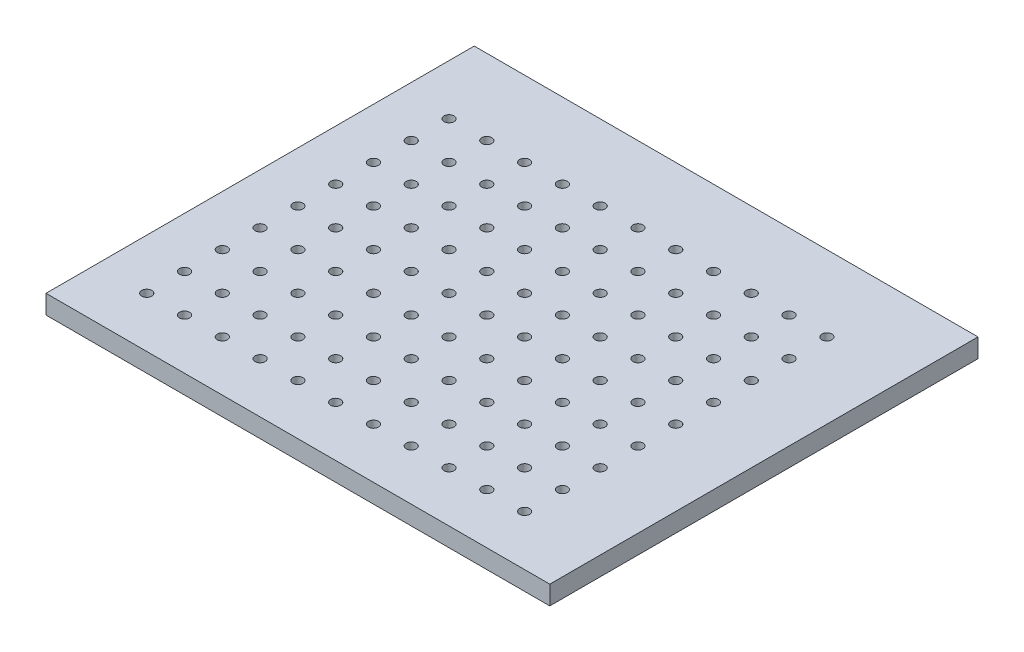
SolidWorks part; units mm, degrees
ref_plane "Plano frontal" through (0, 0, 0) normal (0, 0, 1) x (1, 0, 0)
ref_plane "Plano superior" through (0, 0, 0) normal (0, 1, 0) x (1, 0, 0)
ref_plane "Plano direito" through (0, 0, 0) normal (1, 0, 0) x (0, 0, -1)
sketch "Esboço1" plane through (0, 0, 0) normal (0, 1, 0) x (1, 0, 0)
  line L1 (-200, -170) -> (200, -170)
  line L2 (-200, -170) -> (-200, 170)
  line L3 (-200, 170) -> (200, 170)
  line L4 (200, -170) -> (200, 170)
  line L5 (-200, -170) -> (200, 170) construction
  line L6 (-200, 170) -> (200, -170) construction
  point P0 (0, 0)
  dimension "D1" = 340
  dimension "D2" = 400
extrude "Ressalto-extrusão1" add sketch "Esboço1" along normal blind 15
sketch "Esboço2" plane through (0, 15, 0) normal (0, 1, 0) x (1, 0, 0)
  line L0 (-200, -170) -> (200, -170) construction
  line L1 (-200, 170) -> (-200, -170) construction
  circle A0 centre (-160, -130) radius 4
  dimension "D1" = 8
  dimension "D2" = 40
  dimension "D3" = 40
extrude "Corte-extrusão1" cut sketch "Esboço2" against normal through all
pattern_linear "Padrão linear1" count 11 spacing 30 along (1, 0, 0) count 9 spacing 30 along (0, 0, -1) of "Corte-extrusão1"
